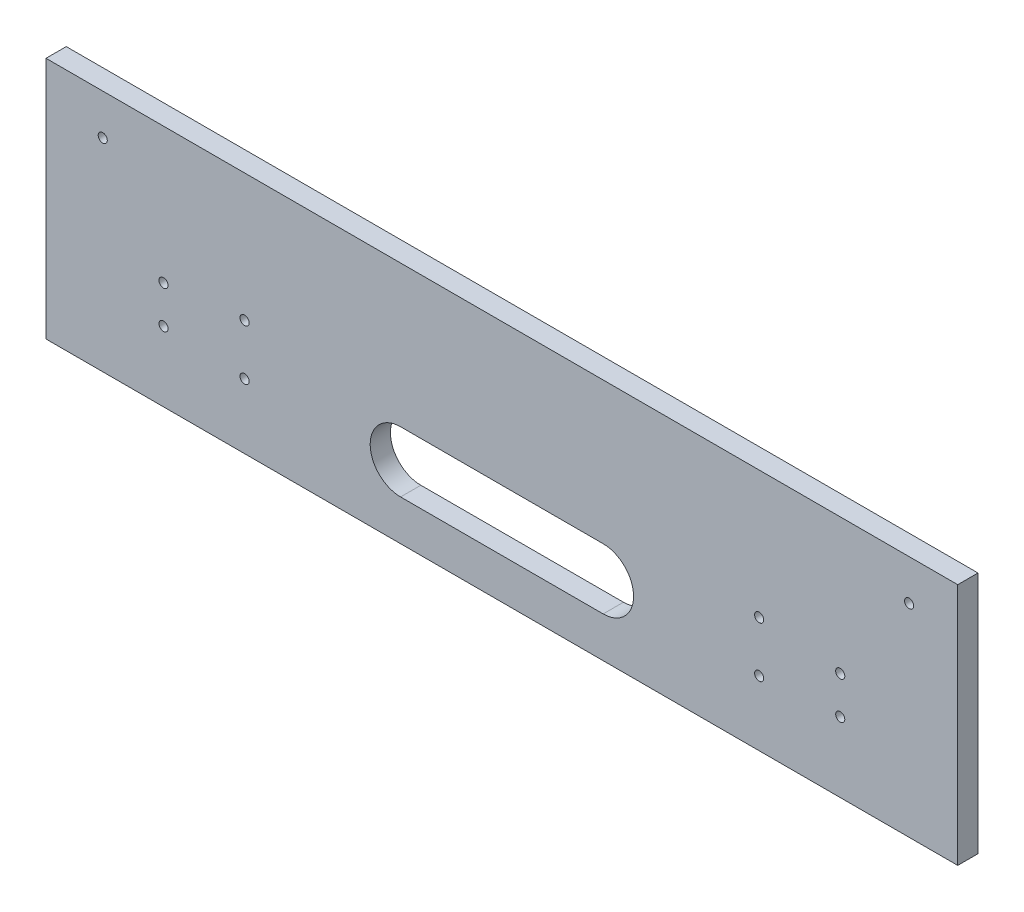
SolidWorks part; units mm, degrees
material "Multistrato di pioppo"
ref_plane "Piano frontale" through (0, 0, 0) normal (0, 0, 1) x (1, 0, 0)
ref_plane "Piano superiore" through (0, 0, 0) normal (0, 1, 0) x (1, 0, 0)
ref_plane "Piano destro" through (0, 0, 0) normal (1, 0, 0) x (0, 0, -1)
sketch "Schizzo1" plane through (0, 0, 0) normal (0, 0, 1) x (1, 0, 0)
  line L1 (-225, 60) -> (225, 60)
  line L2 (-225, 60) -> (-225, -60)
  line L3 (-225, -60) -> (225, -60)
  line L4 (225, 60) -> (225, -60)
  line L5 (-225, 60) -> (225, -60) construction
  line L6 (-225, -60) -> (225, 60) construction
  point P4 (0, 0)
  dimension "D1" = 120
  dimension "D2" = 450
extrude "Estrusione-Estrusione1" add sketch "Schizzo1" along normal blind 10
sketch "Schizzo2" plane through (0, 0, 10) normal (0, 0, 1) x (1, 0, 0)
  line L0 (-50, -25) -> (50, -25) construction
  line L5 (0, -25) -> (0, 0) construction
  line L6 (-225, -60) -> (225, -60) construction
  line L7 (-50, -10) -> (50, -10)
  line L8 (-50, -40) -> (50, -40)
  arc A0 (-50, -10) -> (-50, -40) centre (-50, -25) ccw
  arc A1 (50, -40) -> (50, -10) centre (50, -25) ccw
  point P11 (0, -25)
  dimension "D1" = 130
  dimension "D2" = 30
  dimension "D4" = 20
extrude "Taglio-Estrusione1" cut sketch "Schizzo2" against normal blind 10
sketch "Schizzo3" plane through (0, 0, 0) normal (0, 0, -1) x (-1, 0, 0)
  line L0 (-127, -2) -> (-127, -25) construction
  line L1 (127, -2) -> (127, -25) construction
  line L2 (-225, -60) -> (-225, 60) construction
  line L3 (225, -60) -> (-225, -60) construction
  line L4 (225, 60) -> (225, -60) construction
  line L5 (-185, 40) -> (-205, 40) construction
  circle A0 centre (-167, -7) radius 2.25
  circle A1 centre (-167, -25.5) radius 2.25
  circle A2 centre (167, -7) radius 2.25
  circle A3 centre (167, -25.5) radius 2.25
  circle A5 centre (197, 40) radius 2.25
  circle A7 centre (-201, 40) radius 2.25
  circle A8 centre (-127, -2) radius 2.25 construction
  circle A9 centre (-127, -25) radius 2.25 construction
  circle A10 centre (127, -2) radius 2.25 construction
  circle A11 centre (127, -25) radius 2.25 construction
  point P12 (0, 0)
  point P13 (197, 40)
  dimension "D1" = 4.5
  dimension "D2" = 23
  dimension "D3" = 98
  dimension "D4" = 58
  dimension "D5" = 98
  dimension "D6" = 58
extrude "Taglio-Estrusione2" cut sketch "Schizzo3" against normal blind 10
sketch "Schizzo4" plane through (0, 0, 10) normal (0, 0, 1) x (1, 0, 0)
  line L0 (-127, -28) -> (-127, -3) construction
  line L1 (-225, 60) -> (-225, -60) construction
  line L2 (-225, -60) -> (225, -60) construction
  line L3 (127, -28) -> (127, -3) construction
  line L4 (225, -60) -> (225, 60) construction
  circle A0 centre (-127, -3) radius 2.25
  circle A1 centre (-127, -28) radius 2.25
  circle A2 centre (127, -28) radius 2.25
  circle A3 centre (127, -3) radius 2.25
  dimension "D1" = 4.5
  dimension "D2" = 98
  dimension "D3" = 32
  dimension "D4" = 25
  dimension "D5" = 25
  dimension "D6" = 32
  dimension "D7" = 98
extrude "Taglio-Estrusione3" cut sketch "Schizzo4" against normal blind 10
